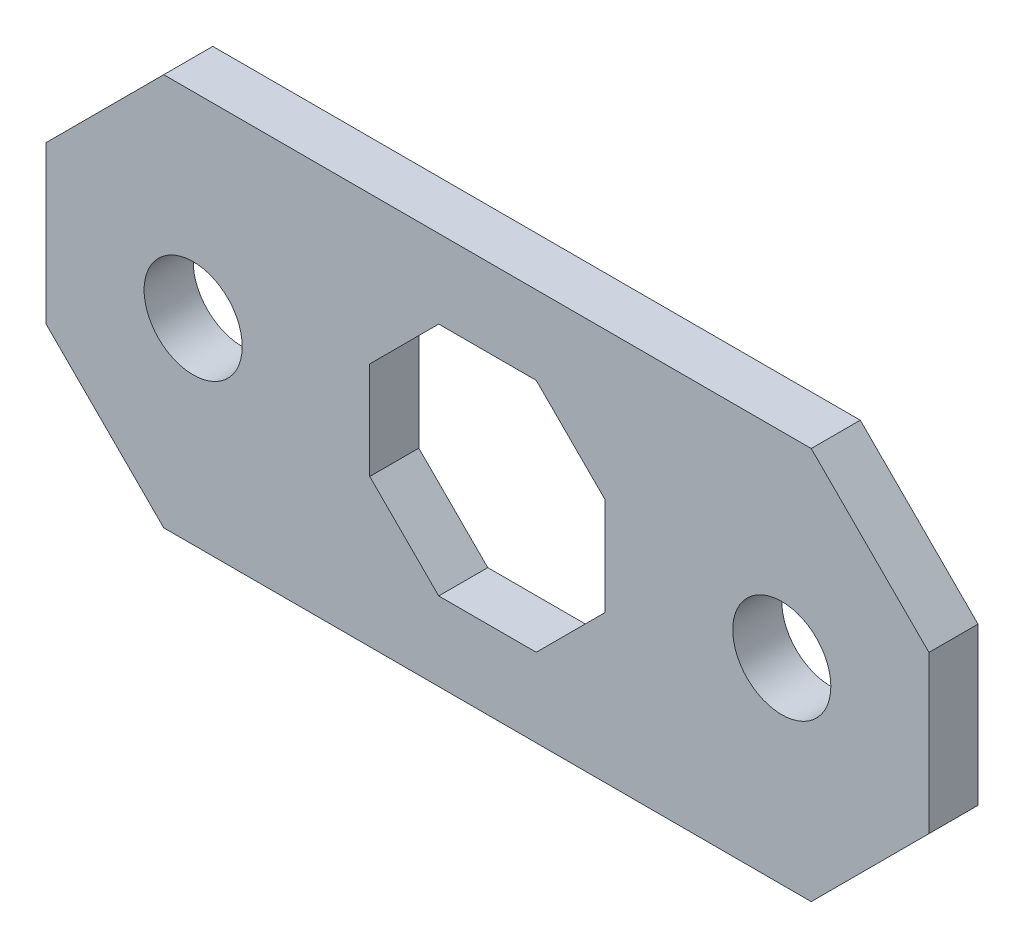
SolidWorks part; units mm, degrees
material "Oak"
ref_plane "Front Plane" through (0, 0, 0) normal (0, 0, 1) x (1, 0, 0)
ref_plane "Top Plane" through (0, 0, 0) normal (0, 1, 0) x (1, 0, 0)
ref_plane "Right Plane" through (0, 0, 0) normal (1, 0, 0) x (0, 0, -1)
sketch "Sketch2" plane through (0, 0, 0) normal (0, 0, 1) x (1, 0, 0)
  line L1 (-28.575, -12.7) -> (28.575, -12.7)
  line L2 (-28.575, -12.7) -> (-28.575, 12.7)
  line L3 (-28.575, 12.7) -> (28.575, 12.7)
  line L4 (28.575, -12.7) -> (28.575, 12.7)
  line L5 (-28.575, -12.7) -> (28.575, 12.7) construction
  line L6 (-28.575, 12.7) -> (28.575, -12.7) construction
  point P0 (0, 0)
extrude "Boss-Extrude1" add sketch "Sketch2" along normal blind 3.175
hole_wizard "Hole1" positions "Sketch4" profile "Sketch3" legacy end condition through all
sketch "Sketch4" plane through (0, 0, 3.175) normal (0, 0, 1) x (1, 0, 0)
  point P0 (-19.05, 0)
  point P2 (19.05, 0)
sketch "Sketch3" plane through (-19.05, 0, 3.175) normal (1, 0, 0) x (0, -1, 0)
  line L0 (0, 0) -> (0, 3.175)
  line L1 (0, 3.175) -> (3.175, 3.175)
  line L2 (3.175, 3.175) -> (3.175, 0)
  line L3 (3.175, 0) -> (0, 0)
  line L4 (0, 110) -> (0, -10) construction
  dimension "Diameter" = 6.35
  dimension "Depth" = 3.175
chamfer "Chamfer1" distance 7.62 angle 45 4 edges at (28.575, 12.7, 1.5875) (-28.575, 12.7, 1.5875) (-28.575, -12.7, 1.5875) (28.575, -12.7, 1.5875)
sketch "Sketch5" plane through (0, 0, 3.175) normal (0, 0, 1) x (1, 0, 0)
  line L1 (7.62, 3.1563) -> (3.1563, 7.62)
  line L2 (3.1563, 7.62) -> (-3.1563, 7.62)
  line L3 (-3.1563, 7.62) -> (-7.62, 3.1563)
  line L4 (-7.62, 3.1563) -> (-7.62, -3.1563)
  line L5 (-7.62, -3.1563) -> (-3.1563, -7.62)
  line L6 (-3.1563, -7.62) -> (3.1563, -7.62)
  line L7 (3.1563, -7.62) -> (7.62, -3.1563)
  line L8 (7.62, -3.1563) -> (7.62, 3.1563)
  circle A0 centre (0, 0) radius 7.62 construction
extrude "Cut-Extrude1" cut sketch "Sketch5" against normal through all
